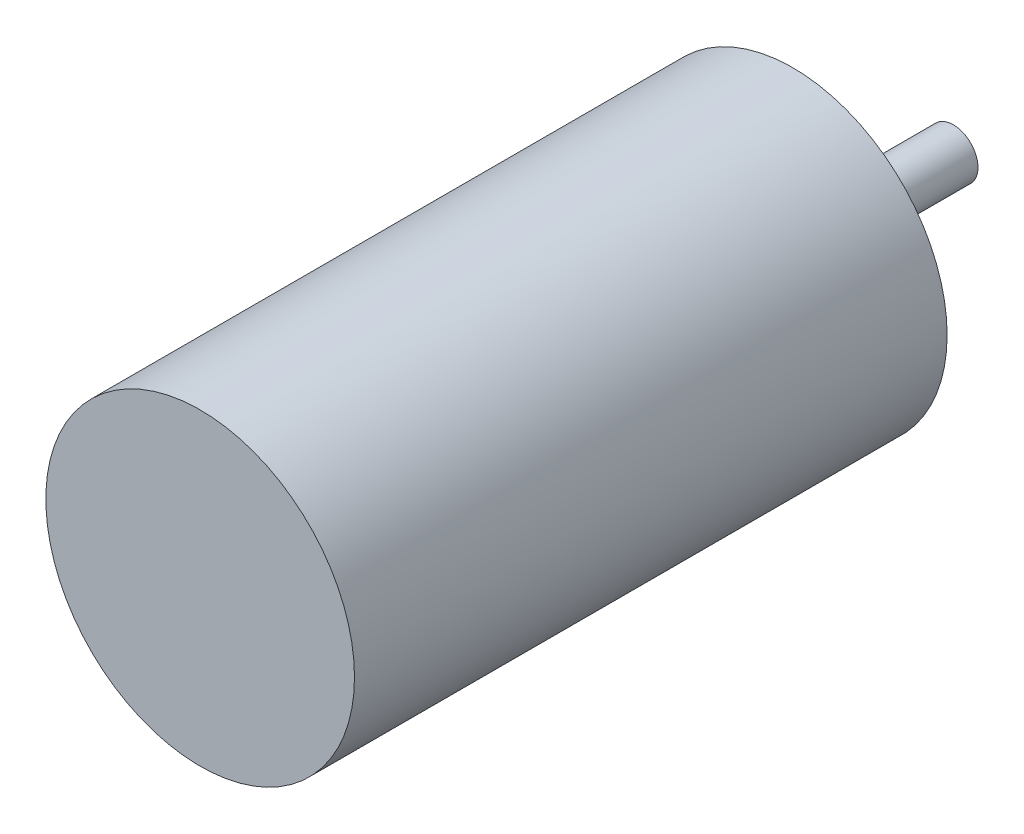
SolidWorks part; units mm, degrees
ref_plane "Front Plane" through (0, 0, 0) normal (0, 0, 1) x (1, 0, 0)
ref_plane "Top Plane" through (0, 0, 0) normal (0, 1, 0) x (1, 0, 0)
ref_plane "Right Plane" through (0, 0, 0) normal (1, 0, 0) x (0, 0, -1)
sketch "Sketch1" plane through (0, 0, 0) normal (1, 0, 0) x (0, 0, -1)
  line L0 (0, 0) -> (0, -2)
  line L1 (0, -2) -> (-10, -2)
  line L2 (-10, -2) -> (-10, -3.5)
  line L3 (-10, -3.5) -> (-13, -3.5)
  line L4 (-13, -3.5) -> (-13, -12.5)
  line L5 (-13, -12.5) -> (-61, -12.5)
  line L6 (-61, -12.5) -> (-61, 0)
  line L7 (-61, 0) -> (0, 0)
  dimension "D1" = 12.5
  dimension "D2" = 48
  dimension "D3" = 2
  dimension "D4" = 10
  dimension "D5" = 3
  dimension "D6" = 3.5
revolve "Revolve1" add sketch "Sketch1" angle 360 about L7
sketch "Sketch2" plane through (0, 0, 13) normal (0, 0, -1) x (-1, 0, 0)
  line L0 (-15.14, 0) -> (21.5661, 0) construction
  line L1 (0, 11.54) -> (0, -14.4671) construction
  point P3 (-8.5, 0)
  point P4 (8.5, 0)
  point P7 (0, 0)
  point P8 (0, 0)
  point P9 (0, 0)
  dimension "D1" = 17
hole_wizard "Tap Drill for M3x0.5 Tap1" positions "Sketch3" profile "Sketch4" hole size "M3x0.5" standard "ANSI Metric"
sketch "Sketch3" plane through (0, 0, 13) normal (0, 0, -1) x (-1, 0, 0)
  point P0 (-8.5, 0)
  point P3 (8.5, 0)
sketch "Sketch4" plane through (8.5, 0, 13) normal (1, 0, 0) x (0, 1, 0)
  line L0 (0, 0) -> (0, 5.7511)
  line L1 (0, 5.7511) -> (1.25, 5)
  line L2 (1.25, 5) -> (1.25, 0)
  line L5 (1.25, 0) -> (0, 0)
  line L10 (0, 5.7511) -> (-1.25, 5) construction
  line L11 (0, -6.35) -> (0, 107.95) construction
  dimension "Hole Dia." = 2.5
  dimension "Hole Depth" = 5
  dimension "Drill Angle" = 118
